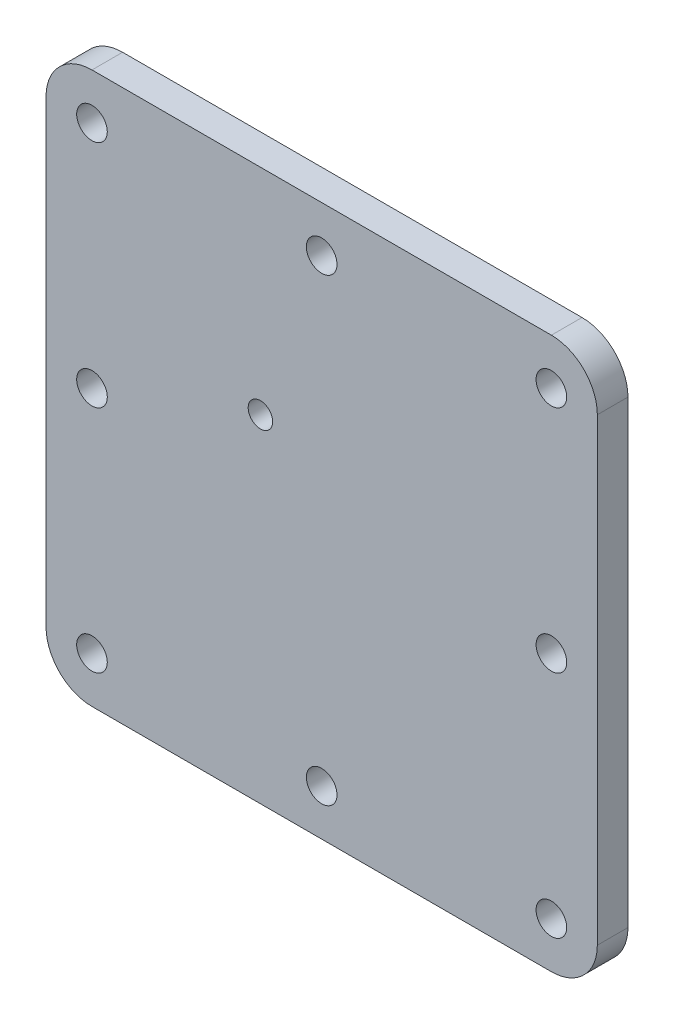
SolidWorks part; units mm, degrees
ref_plane "Front Plane" through (0, 0, 0) normal (0, 0, 1) x (1, 0, 0)
ref_plane "Top Plane" through (0, 0, 0) normal (0, 1, 0) x (1, 0, 0)
ref_plane "Right Plane" through (0, 0, 0) normal (1, 0, 0) x (0, 0, -1)
sketch "Sketch2" plane through (0, 0, 0) normal (0, 0, 1) x (1, 0, 0)
  line L0 (-75, 75) -> (75, 75) construction
  line L1 (-75, 90) -> (75, 90)
  line L2 (-90, 75) -> (-90, -75)
  line L3 (-75, -90) -> (75, -90)
  line L4 (90, 75) -> (90, -75)
  line L5 (-90, 90) -> (90, -90) construction
  line L6 (-90, -90) -> (90, 90) construction
  line L7 (75, 75) -> (75, -75) construction
  line L8 (75, -75) -> (-75, -75) construction
  line L9 (-75, -75) -> (-75, 75) construction
  line L15 (-60, 60) -> (60, -60) construction
  line L16 (-60, -60) -> (60, 60) construction
  arc A0 (-90, -75) -> (-75, -90) centre (-75, -75) ccw
  arc A1 (75, -90) -> (90, -75) centre (75, -75) ccw
  arc A2 (75, 90) -> (90, 75) centre (75, 75) cw
  arc A3 (-75, 90) -> (-90, 75) centre (-75, 75) ccw
  circle A4 centre (-75, 75) radius 5
  circle A5 centre (0, 75) radius 5
  circle A6 centre (75, 75) radius 5
  circle A7 centre (-75, 0) radius 5
  circle A8 centre (0, 0) radius 5 construction
  circle A9 centre (75, 0) radius 5
  circle A10 centre (-75, -75) radius 5
  circle A11 centre (0, -75) radius 5
  circle A12 centre (75, -75) radius 5
  point P0 (0, 0)
  dimension "D3" = 15
  dimension "D4" = 10
  dimension "D1" = 180
  dimension "D2" = 180
  dimension "D8" = 120
  dimension "D7" = 3
extrude "Boss-Extrude1" add sketch "Sketch2" along normal blind 10
sketch "Sketch3" plane through (0, 0, 10) normal (0, 0, 1) x (1, 0, 0)
  line L1 (-50, 50) -> (50, 50) construction
  line L2 (-50, 50) -> (-50, -50) construction
  line L3 (-50, -50) -> (50, -50) construction
  line L4 (50, 50) -> (50, -50) construction
  line L5 (-50, 50) -> (50, -50) construction
  line L6 (-50, -50) -> (50, 50) construction
  line L7 (0, 0) -> (-40, 0) construction
  line L8 (0, 0) -> (0, 40) construction
  line L9 (0, 40) -> (-40, 40) construction
  line L10 (-40, 0) -> (-40, 40) construction
  circle A0 centre (0, 0) radius 4 construction
  point P0 (0, 0)
  dimension "D5" = 8
  dimension "D1" = 100
  dimension "D2" = 100
  dimension "D3" = 40
  dimension "D4" = 40
sketch "Sketch5" plane through (0, 0, 10) normal (0, 0, 1) x (1, 0, 0)
  line L0 (-50, 50) -> (50, -50) construction
  line L1 (0, 0) -> (-40, 0) construction
  circle A0 centre (-20, 20) radius 4
  dimension "D1" = 8
  dimension "D2" = 20
extrude "Cut-Extrude5" cut sketch "Sketch5" against normal blind 10
